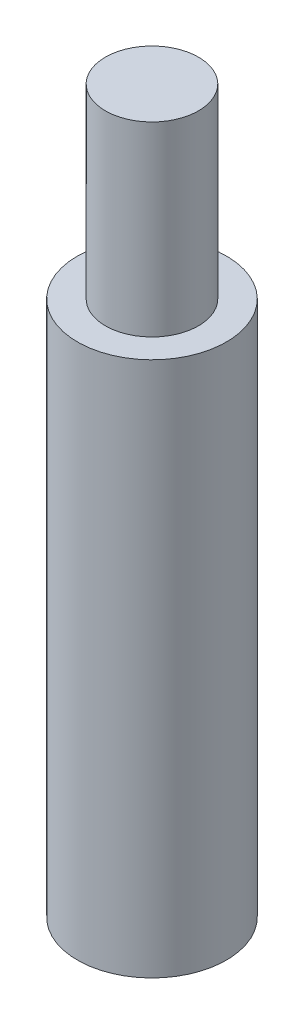
SolidWorks part; units mm, degrees
ref_plane "Front Plane" through (0, 0, 0) normal (0, 0, 1) x (1, 0, 0)
ref_plane "Top Plane" through (0, 0, 0) normal (0, 1, 0) x (1, 0, 0)
ref_plane "Right Plane" through (0, 0, 0) normal (1, 0, 0) x (0, 0, -1)
sketch "Sketch2" plane through (0, 0, 0) normal (0, 0, 1) x (1, 0, 0)
  line L0 (0, 11.5) -> (0, -11.5) construction
  line L1 (0, 0) -> (1, 0)
  line L2 (1, 0) -> (1, -4)
  line L3 (1, -4) -> (1.6, -4)
  line L4 (1.6, -4) -> (1.6, -15.5)
  line L5 (1.6, -15.5) -> (1.05, -15.5)
  line L6 (0, -11.5) -> (1.05, -11.5)
  line L7 (1.05, -11.5) -> (1.05, -15.5)
  line L8 (1.05, 0) -> (1.05, -15.5) construction
  line L9 (0, 0) -> (0, -11.5)
  point P4 (0, 0)
  dimension "D2" = 1.05
  dimension "D3" = 0.05
  dimension "D4" = 1.6
  dimension "D5" = 11.5
  dimension "D6" = 4
revolve "Revolve1" add sketch "Sketch2" angle 360 about L9
